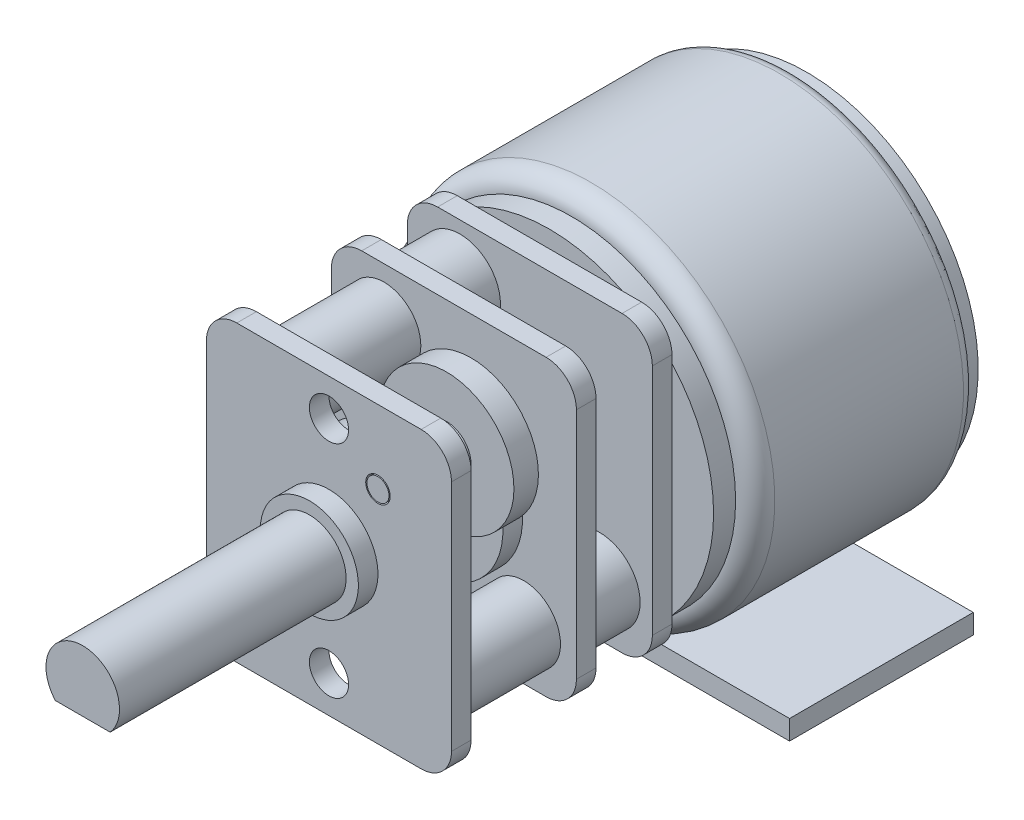
SolidWorks part; units mm, degrees
ref_plane "Front" through (0, 0, 0) normal (0, 0, 1) x (1, 0, 0)
ref_plane "Top" through (0, 0, 0) normal (0, 1, 0) x (1, 0, 0)
ref_plane "Right" through (0, 0, 0) normal (1, 0, 0) x (0, 0, -1)
sketch "Эскиз1" plane through (0, 0, 0) normal (0, 1, 0) x (1, 0, 0)
  line L0 (0, 0) -> (0, -39.2335) construction
  line L1 (0, 0) -> (-0.5, 0)
  line L3 (-0.75, -0.5) -> (-3, -0.5)
  line L4 (-3, -0.5) -> (-3, -1.5)
  line L5 (-3, -1.5) -> (-7, -1.5)
  line L6 (-7, -1.5) -> (-7, -2.1)
  line L8 (-7.5, -2.6) -> (-7.5, -10.3)
  line L10 (-6.7, -11.1) -> (-6.7, -12)
  line L11 (-6.7, -12) -> (-0.75, -12)
  line L12 (0, -12) -> (0, 0)
  line L14 (-7, -2.1) -> (-7, -2.6) construction
  line L15 (-6.7, -11.1) -> (-6.7, -10.3) construction
  line L16 (-6.7, -11.1) -> (-7.5, -11.1) construction
  line L18 (0, -21) -> (-2, -21)
  line L19 (-2, -21) -> (-2, -21.8)
  line L20 (-2, -21.8) -> (-1.5, -21.8)
  line L21 (-1.5, -21.8) -> (-1.5, -31.05)
  line L22 (-1.5, -31.05) -> (0, -31.05)
  line L24 (0, -21) -> (0, -31.05)
  line L25 (-0.75, -12) -> (-0.75, -13.75) construction
  line L26 (0, -14) -> (-0.5, -14) construction
  line L27 (-0.75, -0.5) -> (-0.75, -0.25)
  line L28 (0, -12) -> (-0.75, -12)
  arc A0 (-7, -2.1) -> (-7.5, -2.6) centre (-7, -2.6) ccw
  arc A1 (-7.5, -10.3) -> (-6.7, -11.1) centre (-6.7, -10.3) ccw
  arc A2 (-0.75, -13.75) -> (-0.5, -14) centre (-0.5, -13.75) ccw construction
  arc A3 (-0.5, 0) -> (-0.75, -0.25) centre (-0.5, -0.25) ccw
  dimension "D1" = 6
  dimension "D7" = 0.9
  dimension "D10" = 10.5
  dimension "D16" = 2
  dimension "D4" = 0.5
  dimension "D5" = 0.25
  dimension "D2" = 15
  dimension "D3" = 1
  dimension "D6" = 0.6
  dimension "D8" = 14
  dimension "D9" = 13.4
  dimension "D11" = 19.5
  dimension "D12" = 4
  dimension "D13" = 0.8
  dimension "D14" = 9.25
  dimension "D15" = 3
  dimension "D17" = 1.5
revolve "Motor" add sketch "Эскиз1" angle 360 about L0
sketch "Эскиз2" plane through (0, 0, 31.05) normal (0, 0, 1) x (1, 0, 0)
  line L0 (-1.118, -1) -> (1.118, -1)
  line L1 (-1.6853, 1.5) -> (1.9295, 1.5) construction
  arc A0 (1.118, -1) -> (-1.118, -1) centre (0, 0) ccw
  circle A1 centre (0, 0) radius 1.5 construction
  dimension "D1" = 2.5
extrude "Шпон-паз" cut sketch "Эскиз2" against normal blind 6.5 flip side to cut
sketch "Эскиз7" plane through (0, 0, 12) normal (0, 0, 1) x (1, 0, 0)
  line L1 (3.7627, 6) -> (-3.7627, 6)
  line L2 (5, 4.7627) -> (5, -4.7627)
  line L3 (3.7627, -6) -> (-3.7627, -6)
  line L4 (-5, 4.7627) -> (-5, -4.7627)
  line L5 (5, 6) -> (-5, -6) construction
  line L6 (5, -6) -> (-5, 6) construction
  arc A0 (-3.7627, 6) -> (-5, 4.7627) centre (-3.7627, 4.7627) ccw
  arc A1 (-5, -4.7627) -> (-3.7627, -6) centre (-3.7627, -4.7627) ccw
  arc A2 (3.7627, -6) -> (5, -4.7627) centre (3.7627, -4.7627) ccw
  arc A3 (5, 4.7627) -> (3.7627, 6) centre (3.7627, 4.7627) ccw
  point P0 (0, 0)
  point P18 (4.6376, -5.6376)
  point P19 (-4.6376, 5.6376)
  dimension "D3" = 14.6
  dimension "D4" = 1.2373
  dimension "D1" = 10
  dimension "D2" = 12
extrude "Бобышка-Вытянуть5" add sketch "Эскиз7" along normal blind 0.8
sketch "Эскиз8" plane through (0, 0, 21) normal (0, 0, -1) x (-1, 0, 0)
  line L0 (-5, -4.7627) -> (-5, -4.4598) construction
  line L1 (3.7627, 6) -> (-3.7627, 6)
  line L2 (5, 4.7627) -> (5, -4.7627)
  line L3 (3.7627, -6) -> (-3.7627, -6)
  line L4 (-5, 4.7627) -> (-5, -4.7627)
  line L5 (5, 6) -> (-5, -6) construction
  line L6 (5, -6) -> (-5, 6) construction
  line L7 (3.7627, -6) -> (2.9816, -6) construction
  line L8 (0, -4.5) -> (0, 4.5) construction
  line L9 (2, -3) -> (-2, 3) construction
  arc A0 (-3.7627, 6) -> (-5, 4.7627) centre (-3.7627, 4.7627) ccw
  arc A1 (-5, -4.7627) -> (-3.7627, -6) centre (-3.7627, -4.7627) ccw
  arc A2 (3.7627, -6) -> (5, -4.7627) centre (3.7627, -4.7627) ccw
  arc A3 (5, 4.7627) -> (3.7627, 6) centre (3.7627, 4.7627) ccw
  arc A4 (-5, -4.7627) -> (-3.7627, -6) centre (-3.7627, -4.7627) ccw construction
  circle A5 centre (0, -4.5) radius 0.8
  circle A6 centre (0, 4.5) radius 0.8
  circle A8 centre (2, -3) radius 0.5
  circle A9 centre (-2, 3) radius 0.5
  point P0 (0, 0)
  point P35 (2, -3)
  point P36 (-2, 3)
  dimension "D3" = 1
  dimension "D1" = 1.6
  dimension "D2" = 9
  dimension "D4" = 3
  dimension "D5" = 3
extrude "Бобышка-Вытянуть6" add sketch "Эскиз8" along normal blind 0.8
sketch "Эскиз9" plane through (0, 0, 12.8) normal (0, 0, 1) x (1, 0, 0)
  line L0 (4.5, -2.7511) -> (4.5, -4.8531) construction
  line L1 (2.0633, -5.5) -> (3.9242, -5.5) construction
  line L2 (5, -4.7627) -> (5, 4.7627) construction
  line L3 (-3.7627, -6) -> (3.7627, -6) construction
  line L4 (2.85, -3.85) -> (-2.85, 3.85) construction
  circle A0 centre (2.85, -3.85) radius 1.65
  circle A1 centre (-2.85, 3.85) radius 1.65
  point P14 (0, 0)
  dimension "D1" = 3.3
  dimension "D2" = 0.5
  dimension "D3" = 0.5
extrude "Бобышка-Вытянуть7" add sketch "Эскиз9" along normal blind 2.3
sketch "Эскиз10" plane through (0, 0, 15.1) normal (0, 0, 1) x (1, 0, 0)
  line L1 (3.7627, 6) -> (-3.7627, 6)
  line L2 (5, 4.7627) -> (5, -4.7627)
  line L3 (3.7627, -6) -> (1.2373, -6)
  line L4 (-5, 4.7627) -> (-5, -0.2627)
  line L5 (5, 6) -> (-5, -6) construction
  line L6 (5, -6) -> (-5, 6) construction
  line L8 (3.7627, 6) -> (2.9816, 6) construction
  line L9 (5, -4.7627) -> (5, -4.4598) construction
  line L10 (-3.7627, -1.5) -> (-1.2373, -1.5)
  line L11 (0, -4.7627) -> (0, -2.7373)
  arc A0 (-3.7627, 6) -> (-5, 4.7627) centre (-3.7627, 4.7627) ccw
  arc A2 (3.7627, -6) -> (5, -4.7627) centre (3.7627, -4.7627) ccw
  arc A3 (5, 4.7627) -> (3.7627, 6) centre (3.7627, 4.7627) ccw
  arc A4 (5, 4.7627) -> (3.7627, 6) centre (3.7627, 4.7627) ccw construction
  arc A5 (1.2373, -6) -> (0, -4.7627) centre (1.2373, -4.7627) cw
  arc A6 (-5, -0.2627) -> (-3.7627, -1.5) centre (-3.7627, -0.2627) ccw
  arc A7 (0, -2.7373) -> (-1.2373, -1.5) centre (-1.2373, -2.7373) ccw
  point P0 (0, 0)
  dimension "D1" = 5
  dimension "D2" = 7.5
extrude "Бобышка-Вытянуть8" add sketch "Эскиз10" along normal blind 0.8
sketch "Эскиз11" plane through (0, 0, 15.9) normal (0, 0, 1) x (1, 0, 0)
  circle A0 centre (2.85, -3.85) radius 1.5
  circle A1 centre (-2.85, 3.85) radius 1.5
  circle A4 centre (-2.85, 3.85) radius 1.65 construction
  circle A5 centre (2.85, -3.85) radius 1.65 construction
  dimension "D1" = 3
extrude "Бобышка-Вытянуть9" add sketch "Эскиз11" along normal up to next
sketch "Эскиз12" plane through (0, 0, 0) normal (0, 1, 0) x (1, 0, 0)
  line L0 (0, -20.2) -> (0, -12.8) construction
  line L1 (-1.35, -20.2) -> (-4.35, -20.2) construction
  line L2 (-4.5, -12.8) -> (-1.2, -12.8) construction
  line L3 (0, -20.2) -> (-0.5, -20.2)
  line L4 (-0.5, -20.2) -> (-0.5, -20)
  line L5 (-0.5, -20) -> (-3, -20)
  line L6 (-3, -20) -> (-3, -18.6)
  line L7 (-3, -18.6) -> (-0.5, -18.6)
  line L8 (-0.5, -18.6) -> (-0.5, -18.3)
  line L9 (-0.5, -18.3) -> (-1.5, -18.3)
  line L10 (-1.5, -18.3) -> (-1.5, -16.9)
  line L13 (-1.5, -16.9) -> (-3, -16.9)
  line L14 (-3, -16.9) -> (-3, -16.1)
  line L15 (-3, -16.1) -> (-0.5, -16.1)
  line L16 (-0.5, -16.1) -> (-0.5, -15.9)
  line L17 (-0.5, -15.9) -> (0, -15.9)
  line L18 (0, -15.9) -> (0, -20.2)
  line L19 (-4.35, -15.9) -> (-1.35, -15.9) construction
  line L21 (0, -12.8) -> (-0.75, -12.8)
  line L22 (-0.75, -12.8) -> (-0.75, -13)
  line L23 (-0.75, -13) -> (-1.5, -13)
  line L24 (-1.5, -13) -> (-1.5, -14)
  line L25 (-1.5, -14) -> (-0.75, -14)
  line L26 (-0.75, -14) -> (-0.75, -14.15)
  line L27 (-0.5, -14.4) -> (0, -14.4)
  line L28 (0, -14.4) -> (0, -12.8)
  arc A0 (-0.75, -14.15) -> (-0.5, -14.4) centre (-0.5, -14.15) ccw
  dimension "D8" = 1.5
  dimension "D10" = 0.25
  dimension "D1" = 1
  dimension "D2" = 0.2
  dimension "D3" = 1.4
  dimension "D4" = 0.8
  dimension "D5" = 1.4
  dimension "D6" = 3
  dimension "D7" = 6
  dimension "D9" = 1
  dimension "D11" = 3
  dimension "D12" = 1.6
revolve "Повернуть1" add sketch "Эскиз12" angle 360 about L0
ref_plane "Плоскость2" through (0, 0, 0) normal (-0.8321, 0.5547, 0) x (0, 0, 1)
sketch "Эскиз13" plane through (0, 0, 0) normal (-0.8321, 0.5547, 0) x (0, 0, 1)
  line L0 (21, -3.6056) -> (12.8, -3.6056)
  line L1 (12.8, -0.75) -> (12.8, 0.75) construction
  line L2 (21, -3.6056) -> (21, -3.1556)
  line L3 (21, -3.1556) -> (17.3, -3.1556)
  line L4 (17.3, -3.1556) -> (17.3, -2.6056)
  line L5 (17.3, -2.6056) -> (14, -2.6056)
  line L6 (14, -2.6056) -> (14, -0.8556)
  line L7 (14, -0.8556) -> (13, -0.8556)
  line L8 (13, -0.8556) -> (13, -3.305)
  line L9 (13, -3.305) -> (12.8, -3.305)
  line L10 (12.8, -3.305) -> (12.8, -3.6056)
  line L12 (21, -3.6056) -> (22.843, -3.6056) construction
  dimension "D1" = 0.9
  dimension "D2" = 2
  dimension "D3" = 5.5
  dimension "D4" = 0.2
  dimension "D5" = 1
  dimension "D6" = 3.3
revolve "Повернуть2" add sketch "Эскиз13" angle 360 about L12
sketch "Эскиз14" plane through (0, 0, 0) normal (-0.8321, 0.5547, 0) x (0, 0, 1)
  line L0 (21, 3.6056) -> (15.9, 3.6056)
  line L1 (15.9, -0.5) -> (15.9, 0.5) construction
  line L2 (21, 3.6056) -> (21.7209, 3.6056) construction
  line L3 (21, 3.6056) -> (21, 3.1556)
  line L4 (21, 3.1556) -> (20, 3.1556)
  line L5 (20, 3.1556) -> (20, 2.6056)
  line L6 (20, 2.6056) -> (18.2, 2.6056)
  line L7 (18.2, 2.6056) -> (18.2, 0.8556)
  line L8 (18.2, 0.8556) -> (17.2, 0.8556)
  line L9 (17.2, 0.8556) -> (17.2, 3.1056)
  line L10 (17.2, 3.1056) -> (15.9, 3.1056)
  line L11 (15.9, 3.1056) -> (15.9, 3.6056)
  line L12 (20.2, 6.7363) -> (20.2, -1.1893) construction
  line L13 (15.9, -1.1893) -> (15.9, 6.7363) construction
  dimension "D1" = 0.9
  dimension "D2" = 1
  dimension "D3" = 2
  dimension "D4" = 5.5
  dimension "D5" = 0.2
  dimension "D6" = 2
  dimension "D7" = 1.3
revolve "Повернуть3" add sketch "Эскиз14" angle 360 about L2
ref_plane "Плоскость1" through (0, -7.5, 0) normal (0, -1, 0) x (-1, 0, 0)
sketch "Эскиз4" plane through (0, -7.5, 0) normal (0, -1, 0) x (-1, 0, 0)
  line L0 (0, -2.6) -> (0, -10.3) construction
  line L1 (3.5, -10.2) -> (-8, -10.2)
  line L2 (3.5, -10.2) -> (3.5, -2.7)
  line L3 (3.5, -2.7) -> (-8, -2.7)
  line L4 (-8, -10.2) -> (-8, -2.7)
  line L5 (3.5, -6.45) -> (-8, -6.45) construction
  line L7 (7.5, -10.3) -> (-7.5, -10.3) construction
  line L8 (7.5, -2.6) -> (-7.5, -2.6) construction
  point P5 (0, -6.45)
  dimension "D1" = 7.5
  dimension "D2" = 11.5
  dimension "D3" = 3.5
extrude "Плата" add sketch "Эскиз4" along normal blind 0.8 separate body
sketch "Пайка контактов" plane through (0, -8.3, 0) normal (0, -1, 0) x (1, 0, 0)
  line L0 (-0.75, 7.2) -> (2.25, 7.2) construction
  line L1 (0.75, 5.7) -> (-2.25, 5.7) construction
  line L2 (-0.75, 5.7) -> (-0.75, 7.2) construction
  line L3 (0, 2.6) -> (0, 10.3) construction
  line L5 (-0.75, 7.2) -> (0.75, 5.7) construction
  line L6 (-7.5, 10.3) -> (7.5, 10.3) construction
  line L7 (-7.5, 2.6) -> (7.5, 2.6) construction
  line L8 (7, 5.5333) -> (7, 3.7) construction
  line L9 (7, 7.3667) -> (7, 5.5333) construction
  line L10 (7, 7.3667) -> (7, 9.2) construction
  line L11 (7, 6.45) -> (8, 6.45) construction
  line L12 (8, 2.7) -> (8, 10.2) construction
  circle A0 centre (-2.25, 5.7) radius 0.75
  circle A1 centre (-0.75, 7.2) radius 0.75
  circle A2 centre (0.75, 5.7) radius 0.75
  circle A3 centre (2.25, 7.2) radius 0.75
  circle A4 centre (7, 3.7) radius 0.75
  circle A5 centre (7, 5.5333) radius 0.75
  circle A6 centre (7, 7.3667) radius 0.75
  circle A7 centre (7, 9.2) radius 0.75
  point P13 (0, 6.45)
  point P15 (0, 0)
  point P29 (8, 6.45)
  dimension "D1" = 1.5
  dimension "D4" = 1.5
  dimension "D2" = 3
  dimension "D3" = 1.5
  dimension "D5" = 5.5
  dimension "D6" = 1
extrude "Пайка" add sketch "Пайка контактов" along normal blind 0.7 draft 35
sketch "Эскиз6" plane through (0, -8.3, 0) normal (0, -1, 0) x (1, 0, 0)
  line L0 (5.7717, 10.2) -> (5.7717, 2.7) construction
  line L1 (8, 10.2) -> (-3.5, 10.2) construction
  line L2 (-3.5, 2.7) -> (8, 2.7) construction
  line L3 (-3.5, 8.1932) -> (8, 8.1932) construction
  line L4 (-3.5, 10.2) -> (-3.5, 2.7) construction
  line L5 (8, 2.7) -> (8, 10.2) construction
  text T0 "B1 B2 A1 A2" font "Century Gothic" height 0.85
  text T1 " B1 A2 B2 A1" font "Century Gothic" height 0.8
extrude "Надписи" add sketch "Эскиз6" along normal blind 0.01
